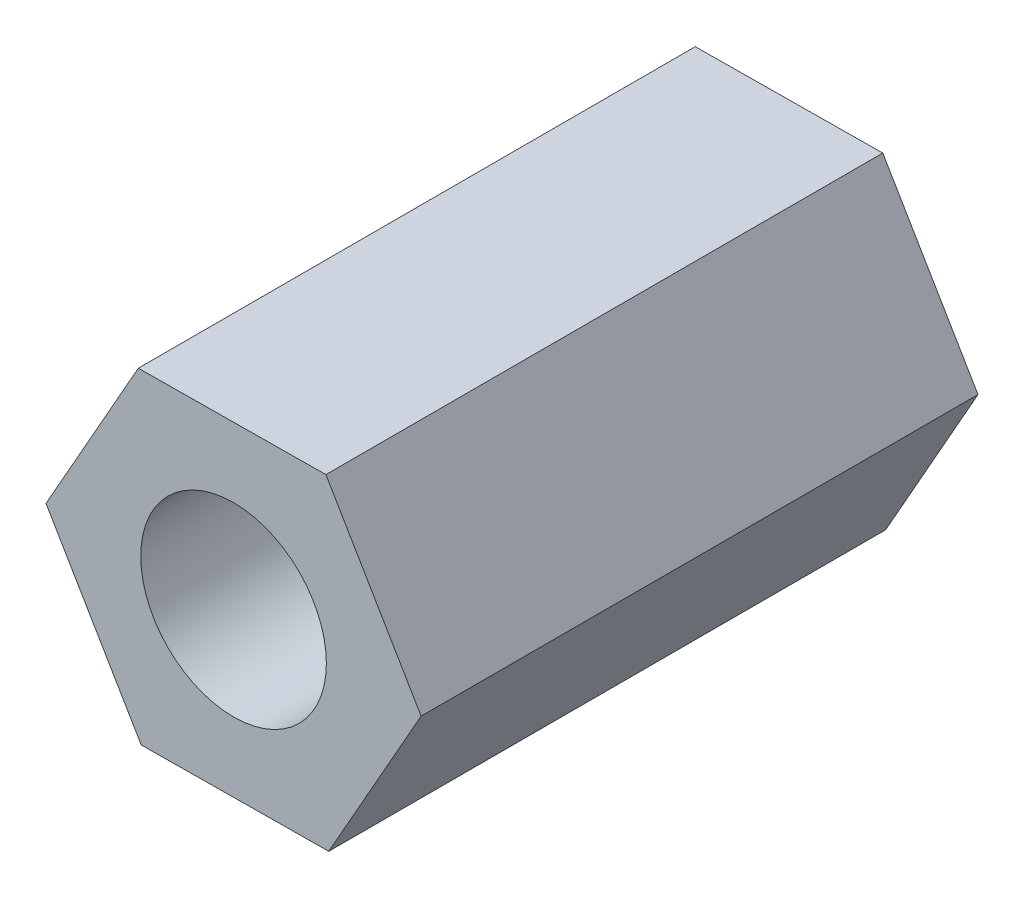
SolidWorks part; units mm, degrees
ref_plane "前视基准面" through (0, 0, 0) normal (0, 0, 1) x (1, 0, 0)
ref_plane "上视基准面" through (0, 0, 0) normal (0, 1, 0) x (1, 0, 0)
ref_plane "右视基准面" through (0, 0, 0) normal (1, 0, 0) x (0, 0, -1)
sketch "草图1" plane through (0, 0, 0) normal (0, 0, 1) x (1, 0, 0)
  line L1 (2.0515, -3.4821) -> (4.0413, 0.0356)
  line L2 (4.0413, 0.0356) -> (1.9898, 3.5177)
  line L3 (1.9898, 3.5177) -> (-2.0515, 3.4821)
  line L4 (-2.0515, 3.4821) -> (-4.0413, -0.0356)
  line L5 (-4.0413, -0.0356) -> (-1.9898, -3.5177)
  line L6 (-1.9898, -3.5177) -> (2.0515, -3.4821)
  circle A0 centre (0, 0) radius 3.5 construction
  circle A1 centre (0, 0) radius 2
extrude "凸台-拉伸1" add sketch "草图1" along normal blind 12
